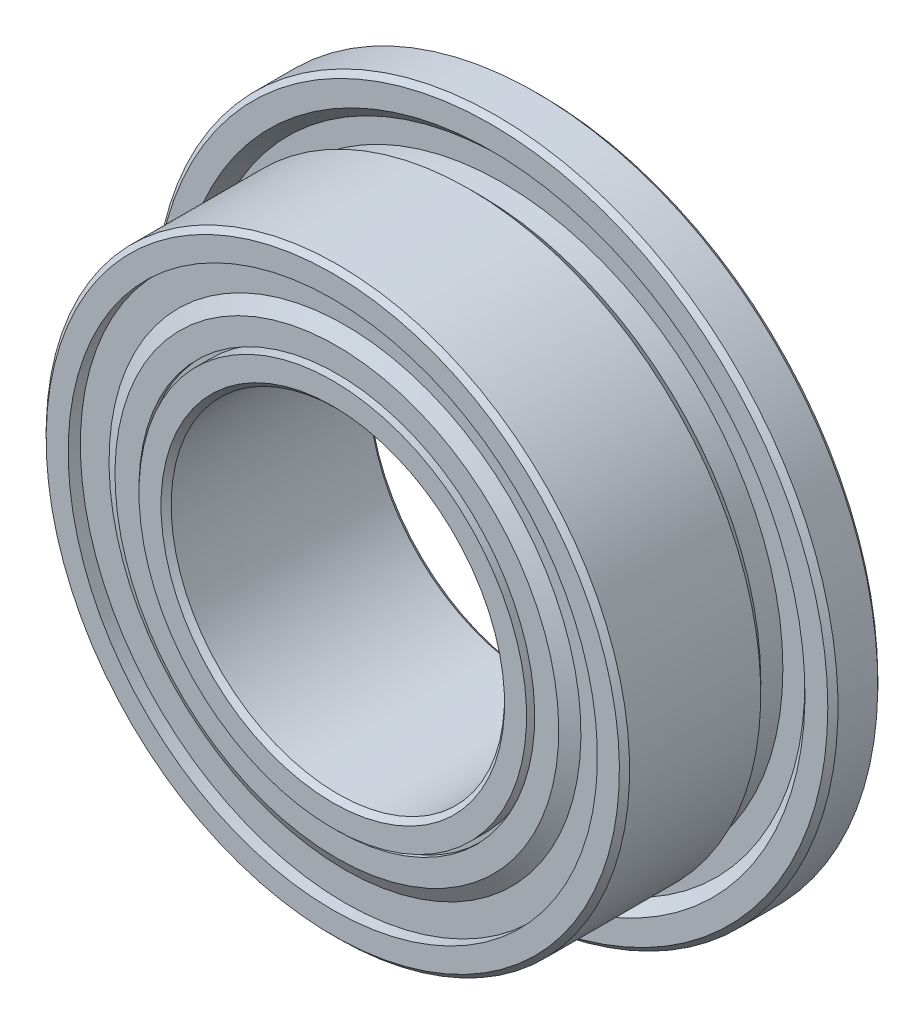
SolidWorks part; units mm, degrees
ref_plane "Front Plane" through (0, 0, 0) normal (0, 0, 1) x (1, 0, 0)
ref_plane "Top Plane" through (0, 0, 0) normal (0, 1, 0) x (1, 0, 0)
ref_plane "Right Plane" through (0, 0, 0) normal (1, 0, 0) x (0, 0, -1)
sketch "Sketch1" plane through (0, 0, 0) normal (1, 0, 0) x (0, 0, -1)
  line L0 (0, 3.5) -> (0, -3.5) construction
  line L1 (-1.25, 3.5) -> (1.25, 3.5) construction
  line L2 (0, 0) -> (1.25, 0) construction
  line L3 (1.25, 4.1) -> (1.25, -4.1) construction
  line L4 (1.25, -4.1) -> (0.65, -4.1) construction
  line L5 (1.25, 2) -> (0, 2) construction
  line L6 (1.25, 2) -> (1.25, -2) construction
  dimension "OD" = 7
  dimension "Width" = 2.5
  dimension "Flange Thickness" = 0.6
  dimension "ID" = 4
  dimension "Flange OD" = 8.2
sketch "Sketch2" plane through (0, 0, 0) normal (1, 0, 0) x (0, 0, -1)
  line L0 (1.25, 4.1) -> (0.65, 4.1)
  line L1 (0.65, 4.1) -> (0.65, 3.7652)
  line L2 (0.3848, 3.5) -> (-1.25, 3.5)
  line L3 (-1.25, 3.5) -> (-1.25, 3.0125)
  line L4 (-1.25, 3.0125) -> (-0.4256, 3.0125)
  line L5 (1.25, 4.1) -> (1.25, -4.1) construction
  line L6 (1.25, 3.0125) -> (1.25, 4.1)
  line L7 (1.25, 2) -> (-1.25, 2)
  line L8 (-1.25, 2) -> (-1.25, 2.4875)
  line L9 (-1.25, 2.4875) -> (-0.4256, 2.4875)
  line L10 (1.25, 2.4875) -> (1.25, 2)
  line L11 (0, 3.5) -> (0, 2) construction
  line L12 (-0.5, 2.75) -> (0.5, 2.75) construction
  line L13 (0.4256, 3.0125) -> (1.25, 3.0125)
  line L14 (0.4256, 2.4875) -> (1.25, 2.4875)
  line L15 (0.65, 3.7652) -> (0.7826, 3.6326)
  line L16 (0.7826, 3.6326) -> (0.7826, 3.3674)
  line L17 (0.7826, 3.3674) -> (0.5174, 3.3674)
  line L18 (0.5174, 3.3674) -> (0.3848, 3.5)
  line L19 (0.65, 3.5) -> (0.7826, 3.3674) construction
  line L20 (0.7826, 3.6326) -> (0.5174, 3.3674) construction
  line L21 (0.3848, 3.5) -> (0.65, 3.5) construction
  line L22 (0.65, 3.5) -> (0.65, 3.7652) construction
  line L23 (-1.25, 0) -> (1.25, 0) construction
  circle A0 centre (0, 2.75) radius 0.5 construction
  arc A1 (-0.4256, 3.0125) -> (0.4256, 3.0125) centre (0, 2.75) cw
  arc A2 (-0.4256, 2.4875) -> (0.4256, 2.4875) centre (0, 2.75) ccw
  dimension "Ball Dia." = 1
  dimension "D2" = 135
  dimension "D3" = 0.375
  dimension "Race Thikness" = 0.4875
  dimension "D4" = 0.525
revolve "Revolve1" add sketch "Sketch2" angle 360 about L2
fillet "Fillet1" radius 0.0609 3 edges at (0, -4.1, -1.25) (0, -4.1, -0.65) (0, -3.5, 1.25) profile chamfer
sketch "Sketch3" plane through (0, 0, 0) normal (0, 0, 1) x (1, 0, 0)
  line L0 (-2, 0) -> (2, 0) construction
  line L1 (-3.5, 0) -> (3.5, 0) construction
  point P5 (0, 0)
  dimension "ID2" = 4
  dimension "OD2" = 7
fillet "Fillet2" radius 0.0609 2 edges at (0, -2, -1.25) (0, -2, 1.25) profile chamfer
sketch "Sketch7" plane through (0, 0, 0) normal (0, 0, 1) x (1, 0, 0)
  line L0 (0, 3.25) -> (0, 2.25)
  line L1 (0, 4.1) -> (0, -4.1) construction
  line L2 (-0.6009, 3.25) -> (0, 0) construction
  line L3 (0, 0) -> (0.6009, 3.25) construction
  line L4 (0.6009, 3.25) -> (-0.6009, 3.25) construction
  circle A0 centre (0, 2.75) radius 0.5 construction
  circle A1 centre (0, 0) radius 3.25 construction
  circle A2 centre (0, 0) radius 2.25 construction
  arc A4 (0, 3.25) -> (0, 2.25) centre (0, 2.75) ccw
  dimension "D1" = 20.951
revolve "Revolve3" add sketch "Sketch7" angle 360 about L0
pattern_circular "CirPattern3" count 13 over 360 about axis through (0, 0, 0) along (0, 0, 1) of bodies 107
sketch "Sketch8" plane through (0, 0, 0) normal (1, 0, 0) x (0, 0, -1)
  line L1 (-1.25, 3.0125) -> (-1.055, 3.0125)
  line L2 (-1.25, 3.0125) -> (-1.25, 3.175)
  line L3 (-1.25, 3.175) -> (-1.055, 3.175)
  line L4 (-1.055, 3.0125) -> (-1.055, 3.175)
  line L5 (1.25, 3.0125) -> (1.055, 3.0125)
  line L6 (1.25, 3.0125) -> (1.25, 3.175)
  line L7 (1.25, 3.175) -> (1.055, 3.175)
  line L8 (1.055, 3.0125) -> (1.055, 3.175)
  line L9 (1.25, 2.4875) -> (1.055, 2.4875)
  line L10 (1.25, 2.4875) -> (1.25, 2.325)
  line L11 (1.25, 2.325) -> (1.055, 2.325)
  line L12 (1.055, 2.4875) -> (1.055, 2.325)
  line L13 (-1.25, 2.4875) -> (-1.055, 2.4875)
  line L14 (-1.25, 2.4875) -> (-1.25, 2.325)
  line L15 (-1.25, 2.325) -> (-1.055, 2.325)
  line L16 (-1.055, 2.4875) -> (-1.055, 2.325)
  dimension "D1" = 0.1625
  dimension "D2" = 0.195
revolve "Cut-Revolve1" cut sketch "Sketch8" angle 360 about L2
sketch "Sketch9" plane through (0, 0, 0) normal (1, 0, 0) x (0, 0, -1)
  line L0 (-1.055, 3.175) -> (-1.055, 2.8179)
  line L1 (-1.055, 2.8179) -> (-1.1525, 2.649)
  line L2 (-1.1525, 2.649) -> (-1.1525, 2.3737)
  line L3 (1.1525, 2.3738) -> (1.1525, 2.325) construction
  line L4 (1.055, 3.175) -> (1.055, 2.8179)
  line L5 (1.055, 2.8179) -> (1.1525, 2.649)
  line L6 (1.1525, 2.649) -> (1.1525, 2.3738)
  line L7 (1.25, 2.325) -> (1.055, 2.325) construction
  line L8 (-1.1038, 3.175) -> (-1.1038, 2.8309)
  line L9 (-1.1038, 2.8309) -> (-1.2013, 2.662)
  line L10 (-1.2013, 2.662) -> (-1.2013, 2.3737)
  line L11 (-1.055, 3.175) -> (-1.1038, 3.175)
  line L12 (-1.1525, 2.3737) -> (-1.2013, 2.3737)
  line L13 (1.1038, 3.175) -> (1.1038, 2.8309)
  line L14 (1.1038, 2.8309) -> (1.2013, 2.662)
  line L15 (1.2013, 2.662) -> (1.2013, 2.3738)
  line L16 (1.055, 3.175) -> (1.1038, 3.175)
  line L17 (1.1525, 2.3738) -> (1.2013, 2.3738)
  line L18 (-1.055, 2.8179) -> (-1.055, 2.5308) construction
  line L19 (1.055, 2.8179) -> (1.055, 3.175) construction
  line L20 (-1.055, 2.325) -> (-1.25, 2.325) construction
  line L22 (-1.1525, 2.3737) -> (-1.1525, 2.325) construction
  dimension "D2" = 150
  dimension "D1" = 150
  dimension "D5" = 0.195
  dimension "D3" = 0.0488
  dimension "D4" = 0.0488
  dimension "D6" = 0.3571
revolve "Revolve4" add sketch "Sketch9" angle 360 about L2
equation "\"D1@Fillet1\"=\"Race Thikness@Sketch2\"/8"
equation "\"ID2@Sketch3\" = \"ID@Sketch1\""
equation "\"OD2@Sketch3\" = \"OD@Sketch1\""
equation "\"D1@Fillet2\"=\"Race Thikness@Sketch2\"/8"
equation "\"D1@CirPattern3\"=360/\"D1@Sketch7\"-4"
equation "\"D1@Sketch8\"=\"Race Thikness@Sketch2\"/3"
equation "\"D2@Sketch8\"=\"Race Thikness@Sketch2\"/2.5"
equation "\"D3@Sketch9\"=\"D5@Sketch9\"/4"
equation "\"D4@Sketch9\"=\"D5@Sketch9\"/4"
equation "\"D1@Sketch9\"=\"D2@Sketch9\""
equation "\"Ball Dia.@Sketch2\" = \"D1@Sketch2\"*.5"
equation "\"D4@Sketch2\"=((\"OD@Sketch1\"-\"ID@Sketch1\")/2)*.35"
